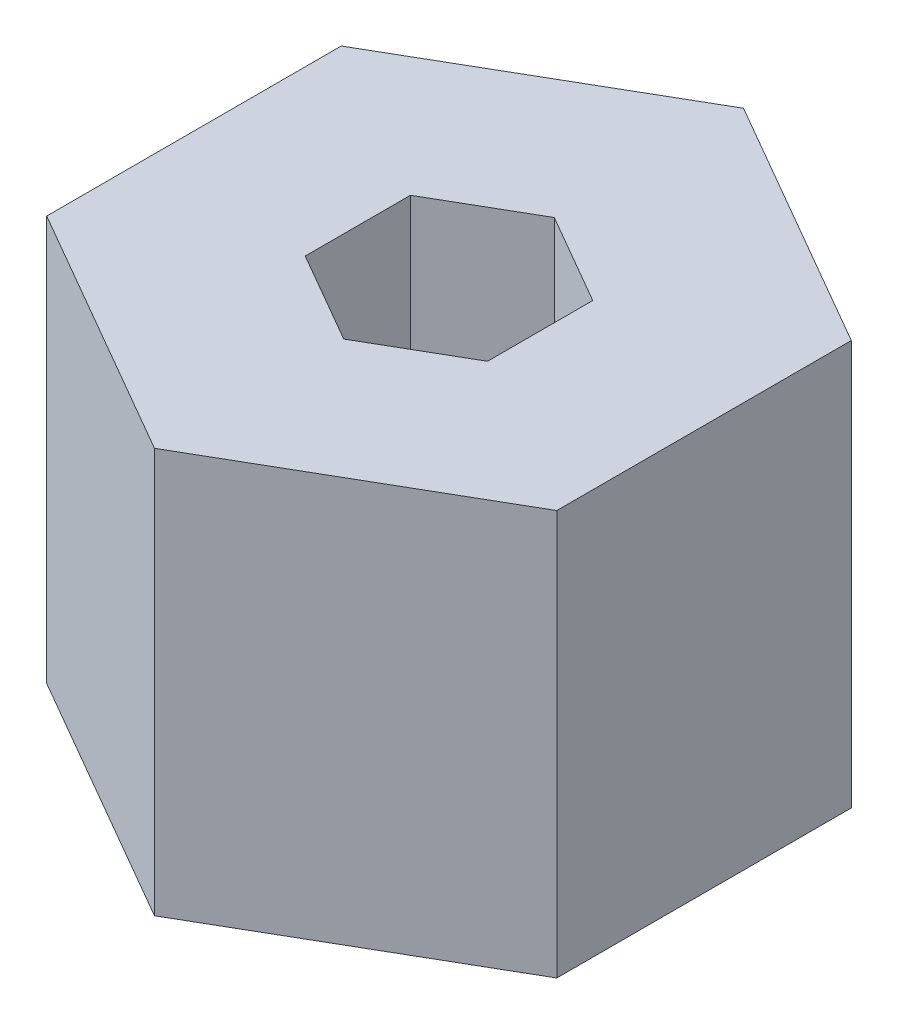
SolidWorks part; units mm, degrees
ref_plane "Front" through (0, 0, 0) normal (0, 0, 1) x (1, 0, 0)
ref_plane "Top" through (0, 0, 0) normal (0, 1, 0) x (1, 0, 0)
ref_plane "Right" through (0, 0, 0) normal (1, 0, 0) x (0, 0, -1)
sketch "Sketch1" plane through (0, 0, 0) normal (0, 1, 0) x (1, 0, 0)
  line L1 (0, 7.2746) -> (-6.3, 3.6373)
  line L2 (-6.3, 3.6373) -> (-6.3, -3.6373)
  line L3 (-6.3, -3.6373) -> (0, -7.2746)
  line L4 (0, -7.2746) -> (6.3, -3.6373)
  line L5 (6.3, -3.6373) -> (6.3, 3.6373)
  line L6 (6.3, 3.6373) -> (0, 7.2746)
  line L7 (0, 2.6) -> (-2.2517, 1.3)
  line L8 (-2.2517, 1.3) -> (-2.2517, -1.3)
  line L9 (-2.2517, -1.3) -> (0, -2.6)
  line L10 (0, -2.6) -> (2.2517, -1.3)
  line L11 (2.2517, -1.3) -> (2.2517, 1.3)
  line L12 (2.2517, 1.3) -> (0, 2.6)
  circle A0 centre (0, 0) radius 6.3 construction
  circle A1 centre (0, 0) radius 2.2517 construction
  dimension "D1" = 12.6
  dimension "D2" = 2.6
extrude "Boss-Extrude1" add sketch "Sketch1" along normal blind 10
